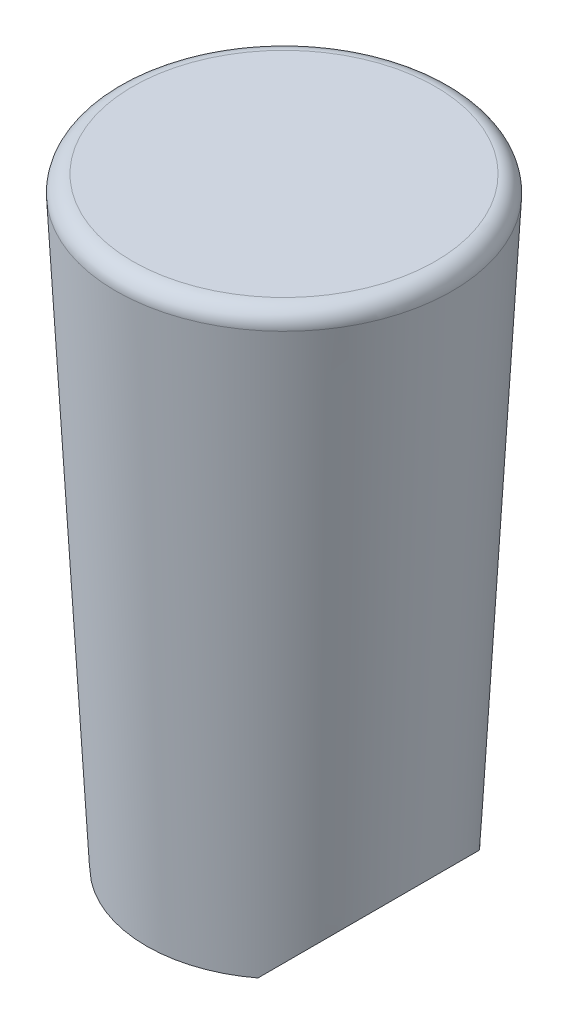
SolidWorks part; units mm, degrees
ref_plane "Front Plane" through (0, 0, 0) normal (0, 0, 1) x (1, 0, 0)
ref_plane "Top Plane" through (0, 0, 0) normal (0, 1, 0) x (1, 0, 0)
ref_plane "Right Plane" through (0, 0, 0) normal (1, 0, 0) x (0, 0, -1)
sketch "Sketch1" plane through (0, 0, 0) normal (0, 1, 0) x (1, 0, 0)
  circle A0 centre (0, 0) radius 8.25
  dimension "D1" = 16.5
extrude "Boss-Extrude1" add sketch "Sketch1" along normal blind 36 draft 3 draft outward yes
sketch "Sketch2" plane through (0, 0, 0) normal (1, 0, 0) x (0, 0, -1)
  line L0 (-8.25, 0) -> (8.25, 0) construction
  line L1 (-5, 0) -> (5, 0)
  line L2 (-5, 0) -> (-5, 25)
  line L3 (-5, 25) -> (5, 25) construction
  line L4 (5, 0) -> (5, 25)
  arc A0 (-5, 25) -> (5, 25) centre (0, 25) cw
  point P8 (0, 30)
  dimension "D1" = 10
  dimension "D2" = 30
extrude "Cut-Extrude1" cut sketch "Sketch2" against normal mid plane 6
sketch "Sketch3" plane through (0, 0, 0) normal (0, 0, 1) x (1, 0, 0)
  line L0 (-5, 0) -> (5, 0)
  line L1 (-8.25, 0) -> (8.25, 0) construction
  line L2 (5, 0) -> (13.8331, 8.8331)
  line L3 (13.8331, 8.8331) -> (13.8331, -5.8695)
  line L4 (13.8331, -5.8695) -> (-13.8331, -5.8695)
  line L5 (-13.8331, -5.8695) -> (-13.8331, 8.8331)
  line L6 (-13.8331, 8.8331) -> (-5, 0)
  dimension "D1" = 10
  dimension "D2" = 45
  dimension "D3" = 45
extrude "Cut-Extrude2" cut sketch "Sketch3" against normal mid plane 46
fillet "Fillet1" radius 1 1 edges at (0, 36, 10.1367)
